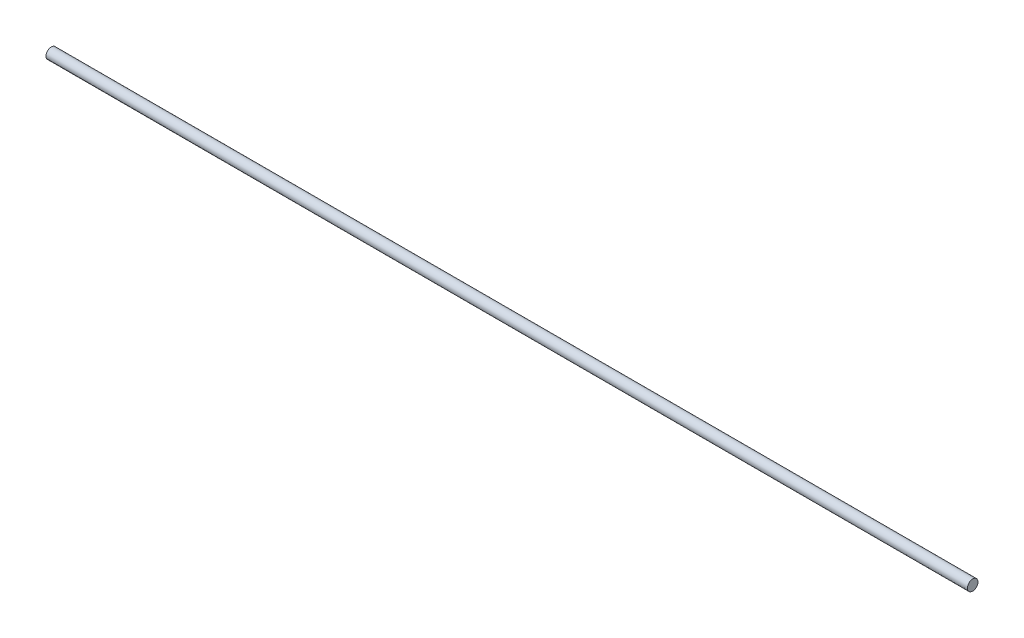
SolidWorks part; units mm, degrees
material "Pure Aluminum, Al"
ref_plane "Front Plane" through (0, 0, 0) normal (0, 0, 1) x (1, 0, 0)
ref_plane "Top Plane" through (0, 0, 0) normal (0, 1, 0) x (1, 0, 0)
ref_plane "Right Plane" through (0, 0, 0) normal (1, 0, 0) x (0, 0, -1)
sketch "Sketch1" plane through (0, 0, 0) normal (1, 0, 0) x (0, 0, -1)
  circle A0 centre (0, 0) radius 6.35
  point P2 (0, 0)
  dimension "D1" = 12.7
extrude "Boss-Extrude1" add sketch "Sketch1" along normal mid plane 1106.424
equation "\"Load Force\"= 400"
equation "\"Young's Modulus E\"= 9.86 * 10 ^ 6"
equation "\"Max Deflection\" = 0.009"
equation "\"Diameter D\"= 0.50"
equation "\"Yield Strength\"= 40000"
equation "\"Area\"= \"Diameter D\" ^ 2 * pi / 4"
equation "\"L\"= \"Max Deflection\" * \"Area\" * \"Young's Modulus E\" / \"Load Force\"''''''"
